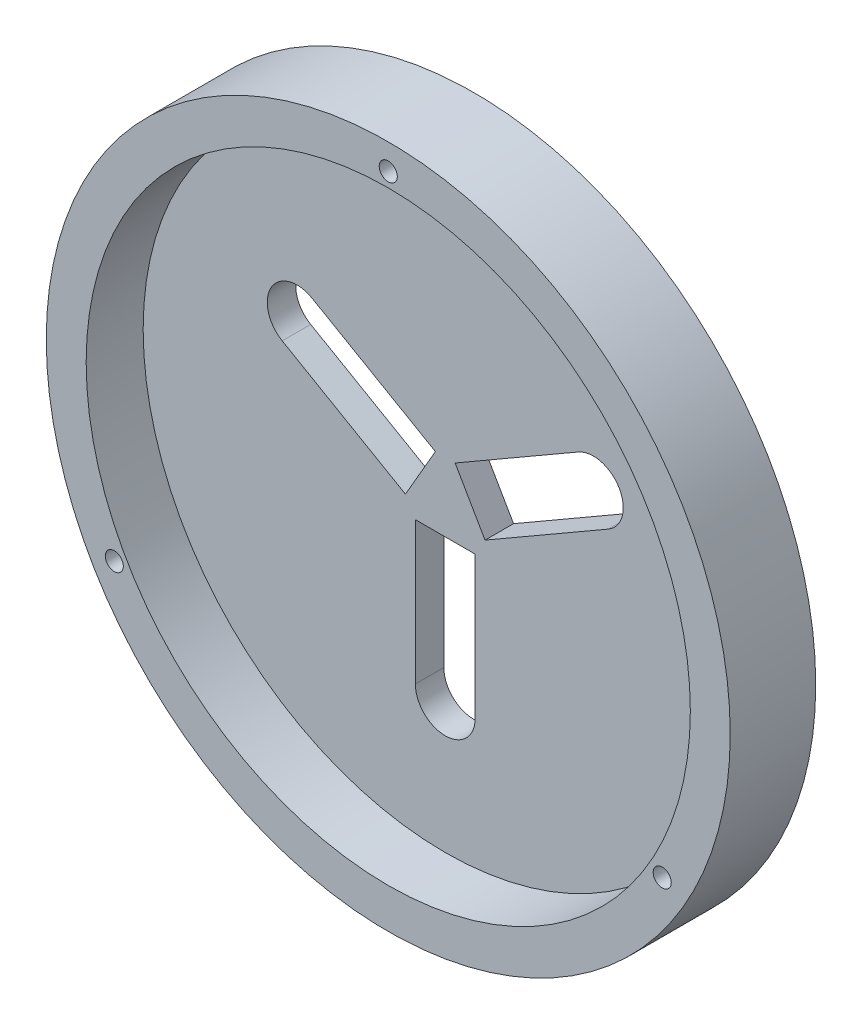
SolidWorks part; units mm, degrees
ref_plane "Alzado" through (0, 0, 0) normal (0, 0, 1) x (1, 0, 0)
ref_plane "Planta" through (0, 0, 0) normal (0, 1, 0) x (1, 0, 0)
ref_plane "Vista lateral" through (0, 0, 0) normal (1, 0, 0) x (0, 0, -1)
sketch "Croquis1" plane through (0, 0, 0) normal (0, 0, 1) x (1, 0, 0)
  circle A0 centre (0, 0) radius 55
  dimension "D1" = 110
extrude "Disco" add sketch "Croquis1" along normal blind 5
sketch "Croquis6" plane through (0, 0, 5) normal (0, 0, 1) x (1, 0, 0)
  line L0 (-5.25, 0) -> (-5.25, -30)
  line L1 (5.25, 0) -> (5.25, -30)
  line L2 (2.625, 4.5466) -> (-23.3558, 19.5466)
  line L3 (-2.625, -4.5466) -> (-28.6058, 10.4534)
  line L4 (2.625, -4.5466) -> (28.6058, 10.4534)
  line L5 (-2.625, 4.5466) -> (23.3558, 19.5466)
  arc A1 (-5.25, 0) -> (5.25, 0) centre (0, 0) cw
  arc A2 (-5.25, -30) -> (5.25, -30) centre (0, -30) ccw
  arc A3 (2.625, 4.5466) -> (-2.625, -4.5466) centre (0, 0) cw
  arc A4 (-23.3558, 19.5466) -> (-28.6058, 10.4534) centre (-25.9808, 15) ccw
  arc A5 (2.625, -4.5466) -> (-2.625, 4.5466) centre (0, 0) cw
  arc A6 (28.6058, 10.4534) -> (23.3558, 19.5466) centre (25.9808, 15) ccw
  point P22 (0, 0)
  dimension "D1" = 30
  dimension "D3" = 5.25
  dimension "D2" = 3
extrude "Cortar-Extruir1" cut sketch "Croquis6" against normal blind 10 contours L2 A4 L3 A3 | L5 A6 L4 A5 | L1 A2 L0 A1
sketch "Croquis7" plane through (0, 0, 5) normal (0, 0, 1) x (1, 0, 0)
  circle A0 centre (0, 0) radius 53
  circle A1 centre (0, 0) radius 60
  circle A2 centre (0, 0) radius 53
  circle M3 centre (0, 0) radius 55
  dimension "D1" = 120
  dimension "D2" = 106
extrude "Saliente-Extruir1" add sketch "Croquis7" along normal blind 10 and the other way through all contours A0 M3 | A1 M3
sketch "Croquis8" plane through (0, 0, 5) normal (0, 0, 1) x (1, 0, 0)
  line L3 (-8.7141, -5.0311) -> (0, 10.0622)
  line L4 (0, 10.0622) -> (8.7141, -5.0311)
  line L5 (8.7141, -5.0311) -> (-8.7141, -5.0311)
extrude "Saliente-Extruir6" add sketch "Croquis8" against normal blind 5
sketch "Croquis9" plane through (0, 0, 15) normal (0, 0, 1) x (1, 0, 0)
  line L0 (0, 0) -> (0, 55.5) construction
  circle A0 centre (0, 55.5) radius 1.5875
  circle A1 centre (48.0644, -27.75) radius 1.5875
  circle A2 centre (-48.0644, -27.75) radius 1.5875
  point P12 (0, 0)
  dimension "D1" = 3
  dimension "D2" = 55.5
extrude "Cortar-Extruir2" cut sketch "Croquis9" against normal through all
sketch "Croquis10" plane through (0, 0, 0) normal (0, 0, -1) x (-1, 0, 0)
  line L0 (0, 0) -> (0, 55.5) construction
  circle A0 centre (0, 55.5) radius 3
  circle A1 centre (48.0644, -27.75) radius 3
  circle A2 centre (-48.0644, -27.75) radius 3
  point P11 (0, 0)
  dimension "D1" = 6
  dimension "D3" = 55.5
  dimension "D2" = 3
extrude "Cortar-Extruir3" cut sketch "Croquis10" against normal blind 3
